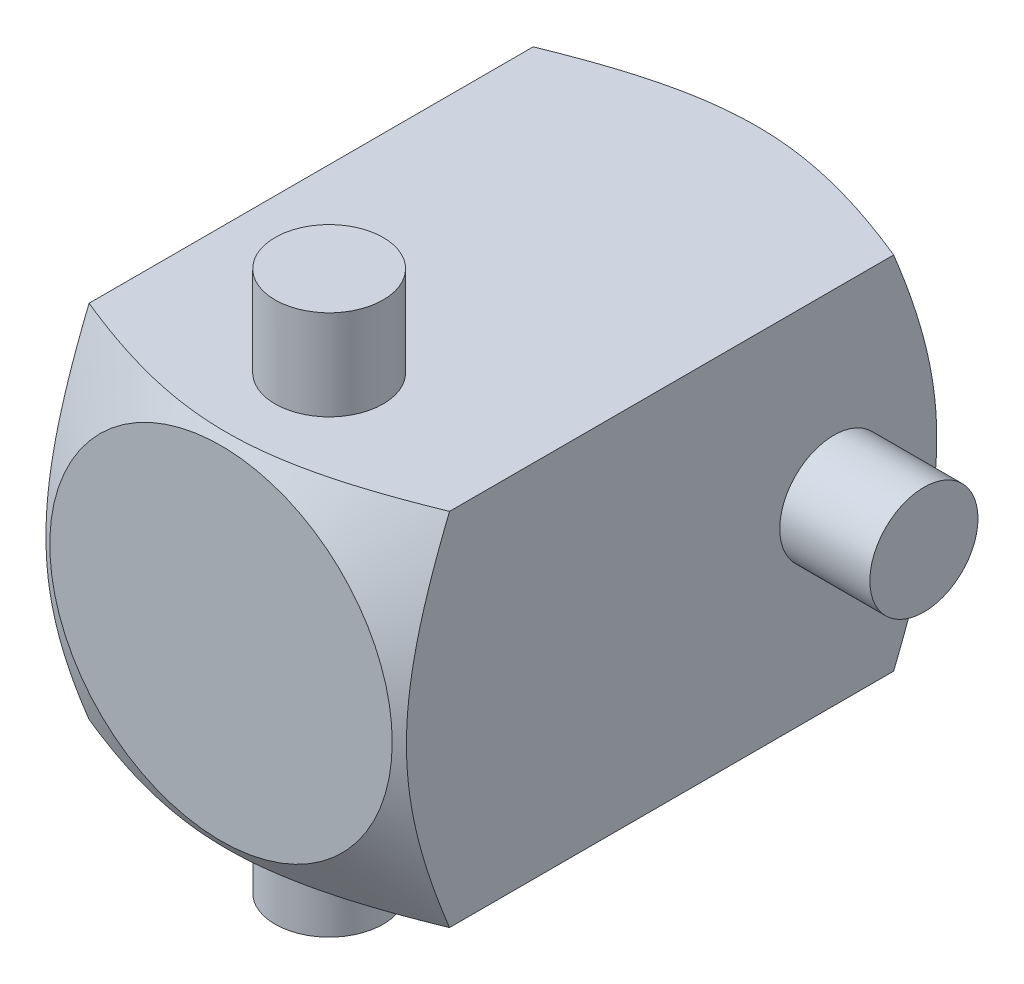
SolidWorks part; units mm, degrees
ref_plane "Ön Düzlem" through (0, 0, 0) normal (0, 0, 1) x (1, 0, 0)
ref_plane "Üst Düzlem" through (0, 0, 0) normal (0, 1, 0) x (1, 0, 0)
ref_plane "Sağ Düzlem" through (0, 0, 0) normal (1, 0, 0) x (0, 0, -1)
sketch "Sketch1" plane through (0, 0, 0) normal (0, 0, 1) x (1, 0, 0)
  line L1 (5, 5) -> (-5, 5)
  line L2 (5, 5) -> (5, -5)
  line L3 (5, -5) -> (-5, -5)
  line L4 (-5, 5) -> (-5, -5)
  line L5 (5, 5) -> (-5, -5) construction
  line L6 (5, -5) -> (-5, 5) construction
  point P0 (0, 0)
  dimension "D1" = 10
  dimension "D2" = 10
extrude "Boss-Extrude1" add sketch "Sketch1" along normal blind 15
ref_axis "Axis1" through (0, 0, 15.75) along (0, 0, -1)
sketch "Sketch2" plane through (0, 0, 0) normal (0, 1, 0) x (1, 0, 0)
  line L0 (-4.75, 0) -> (-15.04, 0)
  line L1 (5, 0) -> (-5, 0) construction
  line L2 (-15.04, 0) -> (-15.04, -15)
  line L3 (-4.75, -15) -> (-15.04, -15)
  line L4 (5, -15) -> (-5, -15) construction
  line L5 (-4.75, -15) -> (-12.5, -10.5255)
  line L6 (-12.5, -10.5255) -> (-12.5, -4.4745)
  line L7 (-12.5, -4.4745) -> (-4.75, 0)
  dimension "D1" = 0.25
  dimension "D2" = 0.25
  dimension "D3" = 2.54
  dimension "D4" = 30
  dimension "D5" = 30
  dimension "D6" = 7.5
revolve "Cut-Revolve1" cut sketch "Sketch2" angle 360 about axis through (0, 0, 15.75) along (0, 0, -1)
sketch "Sketch3" plane through (0, 0, 0) normal (0, 1, 0) x (1, 0, 0)
  line L0 (-4.75, -15) -> (4.75, -15) construction
  line L1 (-5, -13.6599) -> (-5, -1.3401) construction
  circle A0 centre (0, -12) radius 1.5
  dimension "D1" = 3
  dimension "D2" = 3
  dimension "D3" = 5
extrude "Boss-Extrude2" add sketch "Sketch3" along normal mid plane 15
sketch "Sketch4" plane through (0, 0, 0) normal (1, 0, 0) x (0, 0, -1)
  line L0 (0, -4.75) -> (0, 4.75) construction
  line L1 (-13.6599, -5) -> (-1.3401, -5) construction
  circle A0 centre (-3, 0) radius 1.5
  dimension "D1" = 3
  dimension "D2" = 3
  dimension "D3" = 5
extrude "Boss-Extrude3" add sketch "Sketch4" along normal mid plane 15
